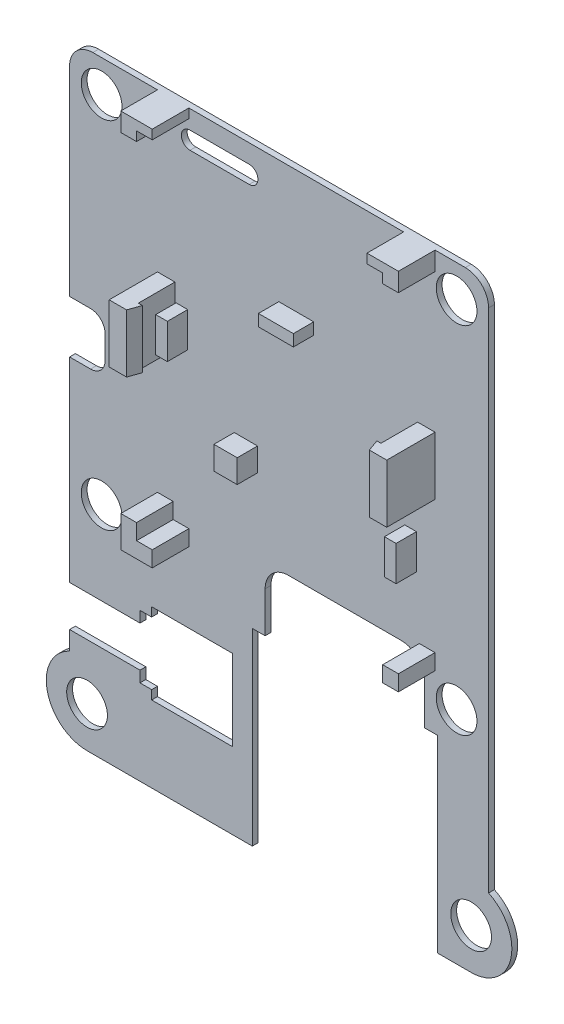
SolidWorks part; units mm, degrees
ref_plane "Front Plane" through (0, 0, 0) normal (0, 0, 1) x (1, 0, 0)
ref_plane "Top Plane" through (0, 0, 0) normal (0, 1, 0) x (1, 0, 0)
ref_plane "Right Plane" through (0, 0, 0) normal (1, 0, 0) x (0, 0, -1)
sketch "Sketch1" plane through (0, 0, 0) normal (0, 0, 1) x (1, 0, 0)
  line L9 (18, -18) -> (-18, -18)
  line L14 (16, 18) -> (-16, 18)
  line L15 (-18, 16) -> (-18, -1.15)
  line L16 (-18, -1.15) -> (-16.2, -1.15)
  line L17 (-14.95, -2.4) -> (-14.95, -4.4)
  line L18 (-16.2, -5.65) -> (-18, -5.65)
  line L19 (-18, -5.65) -> (-18, -18)
  line L20 (-18, -18) -> (-1.2, -18)
  line L21 (-1.2, -18) -> (-1.2, -14.5)
  line L22 (0.8, -12.5) -> (10.5, -12.5)
  line L23 (12.5, -14.5) -> (12.5, -18)
  line L24 (12.5, -18) -> (18, -18)
  line L25 (18, -18) -> (18, 16)
  line L26 (16, 18) -> (-16, 18)
  line L27 (-18, 16) -> (-18, -1.15)
  line L28 (-18, -1.15) -> (-16.2, -1.15)
  line L29 (-14.95, -2.4) -> (-14.95, -4.4)
  line L30 (-16.2, -5.65) -> (-18, -5.65)
  line L31 (-18, -5.65) -> (-18, -18)
  line L32 (-18, -18) -> (-1.2, -18)
  line L33 (-1.2, -18) -> (-1.2, -14.5)
  line L34 (0.8, -12.5) -> (10.5, -12.5)
  line L35 (12.5, -14.5) -> (12.5, -18)
  line L36 (12.5, -18) -> (18, -18)
  line L37 (18, -18) -> (18, 16)
  line L41 (13.6, -18) -> (13.6, -34.2)
  line L42 (13.6, -34.2) -> (16.5, -34.2)
  line L43 (18, -27.5377) -> (18, -18)
  line L44 (18, -18) -> (13.6, -18)
  line L46 (13.6, -18) -> (13.6, -34.2)
  line L47 (13.6, -34.2) -> (16.5, -34.2)
  line L48 (18, -27.5377) -> (18, -18)
  line L49 (18, -18) -> (13.6, -18)
  line L66 (-2.3, -18) -> (-18, -18)
  line L153 (-11.95, -22.43) -> (-11.95, -21.48)
  line L154 (-11.95, -21.48) -> (-10.95, -21.48)
  line L155 (-10.95, -21.48) -> (-10.95, -20.71)
  line L156 (-10.95, -20.71) -> (-4.01, -20.71)
  line L157 (-4.01, -20.71) -> (-4.01, -27.65)
  line L158 (-4.01, -27.65) -> (-10.95, -27.65)
  line L159 (-10.95, -27.65) -> (-10.95, -26.88)
  line L160 (-10.95, -26.88) -> (-11.95, -26.88)
  line L161 (-11.95, -26.88) -> (-11.95, -25.93)
  line L162 (-11.95, -25.93) -> (-18, -25.93)
  line L163 (-18, -25.93) -> (-18, -27.5377)
  line L164 (-16.5, -34.2) -> (-2.3, -34.2)
  line L165 (-2.3, -34.2) -> (-2.3, -18)
  line L166 (-2.3, -18) -> (-18, -18)
  line L167 (-18, -18) -> (-18, -22.43)
  line L168 (-18, -22.43) -> (-11.95, -22.43)
  line L169 (-11.95, -22.43) -> (-11.95, -21.48)
  line L170 (-11.95, -21.48) -> (-10.95, -21.48)
  line L171 (-10.95, -21.48) -> (-10.95, -20.71)
  line L172 (-10.95, -20.71) -> (-4.01, -20.71)
  line L173 (-4.01, -20.71) -> (-4.01, -27.65)
  line L174 (-4.01, -27.65) -> (-10.95, -27.65)
  line L175 (-10.95, -27.65) -> (-10.95, -26.88)
  line L176 (-10.95, -26.88) -> (-11.95, -26.88)
  line L177 (-11.95, -26.88) -> (-11.95, -25.93)
  line L178 (-11.95, -25.93) -> (-18, -25.93)
  line L179 (-18, -25.93) -> (-18, -27.5377)
  line L180 (-16.5, -34.2) -> (-2.3, -34.2)
  line L181 (-2.3, -34.2) -> (-2.3, -18)
  line L182 (-2.3, -18) -> (-18, -18)
  line L183 (-18, -18) -> (-18, -22.43)
  line L184 (-18, -22.43) -> (-11.95, -22.43)
  line L229 (-7.65, 14.9) -> (-2.57, 14.9) construction
  line L230 (-7.65, 16.4) -> (-2.57, 16.4) construction
  line L231 (-7.65, 16.4) -> (-2.57, 16.4)
  line L232 (-7.65, 14.9) -> (-2.57, 14.9)
  circle A2 centre (16.5, -30.7) radius 1.5 construction
  arc A3 (16.5, -34.2) -> (18, -27.5377) centre (16.5, -30.7) ccw
  circle A4 centre (15.25, -15.25) radius 1.75 construction
  circle A5 centre (15.25, 15.25) radius 1.75 construction
  circle A6 centre (-15.25, -15.25) radius 1.75 construction
  arc A7 (-16, 18) -> (-18, 16) centre (-16, 16) ccw
  arc A8 (-14.95, -2.4) -> (-16.2, -1.15) centre (-16.2, -2.4) ccw
  arc A9 (-16.2, -5.65) -> (-14.95, -4.4) centre (-16.2, -4.4) ccw
  arc A10 (0.8, -12.5) -> (-1.2, -14.5) centre (0.8, -14.5) ccw
  arc A11 (12.5, -14.5) -> (10.5, -12.5) centre (10.5, -14.5) ccw
  arc A12 (18, 16) -> (16, 18) centre (16, 16) ccw
  arc A14 (-16, 18) -> (-18, 16) centre (-16, 16) ccw
  arc A15 (-14.95, -2.4) -> (-16.2, -1.15) centre (-16.2, -2.4) ccw
  arc A16 (-16.2, -5.65) -> (-14.95, -4.4) centre (-16.2, -4.4) ccw
  arc A17 (0.8, -12.5) -> (-1.2, -14.5) centre (0.8, -14.5) ccw
  arc A19 (12.5, -14.5) -> (10.5, -12.5) centre (10.5, -14.5) ccw
  arc A20 (18, 16) -> (16, 18) centre (16, 16) ccw
  circle A21 centre (-15.25, 15.25) radius 1.75 construction
  arc A22 (16.5, -34.2) -> (18, -27.5377) centre (16.5, -30.7) ccw
  circle A23 centre (15.25, -15.25) radius 1.75
  circle A24 centre (15.25, 15.25) radius 1.75
  circle A25 centre (-15.25, -15.25) radius 1.75
  circle A26 centre (-15.25, 15.25) radius 1.75
  circle A36 centre (16.5, -30.7) radius 1.5
  circle A54 centre (-16.5, -30.7) radius 1.5 construction
  arc A55 (-18, -27.5377) -> (-16.5, -34.2) centre (-16.5, -30.7) ccw
  arc A56 (-18, -27.5377) -> (-16.5, -34.2) centre (-16.5, -30.7) ccw
  circle A57 centre (-16.5, -30.7) radius 1.5
  arc A62 (-2.57, 14.9) -> (-2.57, 16.4) centre (-2.57, 15.65) ccw construction
  arc A63 (-7.65, 16.4) -> (-7.65, 14.9) centre (-7.65, 15.65) ccw construction
  arc A64 (-7.65, 16.4) -> (-7.65, 14.9) centre (-7.65, 15.65) ccw
  arc A65 (-2.57, 14.9) -> (-2.57, 16.4) centre (-2.57, 15.65) ccw
  circle A69 centre (-16.5, -30.7) radius 1.75
  circle A70 centre (16.5, -30.7) radius 1.75
  dimension "D1" = 0
  dimension "D2" = 0
  dimension "D3" = 0
extrude "Base shape" add sketch "Sketch1" along normal blind 0.5
sketch "Sketch2" plane through (0, 0, 0.5) normal (0, 0, 1) x (1, 0, 0)
  line L0 (1.475, 16.95) -> (1.475, -13.05) construction
  line L1 (-7.85, 1.45) -> (-8.85, 1.45) construction
  line L2 (-0.025, 7.45) -> (2.975, 7.45)
  line L3 (-0.025, 7.45) -> (-0.025, 6.45)
  line L4 (11.8, 16.95) -> (-8.85, 16.95)
  line L5 (-8.85, 16.95) -> (-8.85, -13.05)
  line L6 (-8.85, -13.05) -> (11.8, -13.05)
  line L7 (11.8, -13.05) -> (11.8, 16.95)
  line L8 (11.8, 16.95) -> (-8.85, 16.95)
  line L9 (-8.85, 16.95) -> (-8.85, -13.05)
  line L10 (-8.85, -13.05) -> (11.8, -13.05)
  line L11 (11.8, -13.05) -> (11.8, 16.95)
  line L12 (-0.025, 6.45) -> (2.975, 6.45)
  line L13 (2.975, 7.45) -> (2.975, 6.45)
  line L14 (-0.025, 7.45) -> (2.975, 6.45) construction
  line L15 (-0.025, 6.45) -> (2.975, 7.45) construction
  line L16 (-8.85, 2.95) -> (-7.85, 2.95)
  line L17 (-8.85, 2.95) -> (-8.85, -0.05)
  line L18 (-8.85, -0.05) -> (-7.85, -0.05)
  line L19 (-7.85, 2.95) -> (-7.85, -0.05)
  line L20 (-3.85, -4.2) -> (-1.85, -4.2)
  line L21 (-3.85, -4.2) -> (-3.85, -6.2)
  line L22 (-3.85, -6.2) -> (-1.85, -6.2)
  line L23 (-1.85, -4.2) -> (-1.85, -6.2)
  line L24 (11.8, -3.75) -> (10.8, -3.75)
  line L25 (11.8, -3.75) -> (11.8, -6.75)
  line L26 (11.8, -6.75) -> (10.8, -6.75)
  line L27 (10.8, -3.75) -> (10.8, -6.75)
  line L28 (11.8, 1.95) -> (10.8, 1.95)
  line L29 (11.8, 1.95) -> (11.8, -1.05)
  line L30 (11.8, -1.05) -> (10.8, -1.05)
  line L31 (10.8, 1.95) -> (10.8, -1.05)
  line L32 (-3.85, -5.2) -> (-1.85, -5.2) construction
  line L33 (-2.85, -4.2) -> (-2.85, -6.2) construction
  line L34 (10.8, 0.45) -> (11.8, 0.45) construction
  line L35 (10.8, -5.25) -> (11.8, -5.25) construction
  point P6 (1.475, 6.95)
  dimension "D2" = 3
  dimension "D3" = 1
  dimension "D4" = 10
  dimension "D5" = 7.8
  dimension "D6" = 16.5
  dimension "D7" = 7.85
  dimension "D8" = 6
  dimension "D9" = 2
  dimension "D10" = 15.5
  dimension "D1" = 0
extrude "RX supports" add sketch "Sketch2" along normal blind 1.75 contours L13 L2 L3 L12 | L19 L16 L9 L18 | L23 L20 L21 L22 | L28 L31 L30 L11 | L24 L27 L26 L11
sketch "Sketch3" plane through (0, 0, 0.5) normal (0, 0, 1) x (1, 0, 0)
  line L0 (-8.85, 1.95) -> (11.8, 1.95) construction
  line L1 (1.475, 16.95) -> (1.475, -13.05) construction
  line L2 (-8.95, 4.45) -> (-10.45, 4.45)
  line L3 (-8.95, 4.45) -> (-8.95, -0.55)
  line L4 (11.8, 16.95) -> (-8.85, 16.95)
  line L5 (-8.85, 16.95) -> (-8.85, -13.05)
  line L6 (-8.85, -13.05) -> (11.8, -13.05)
  line L7 (11.8, -13.05) -> (11.8, 16.95)
  line L8 (11.8, 16.95) -> (-8.85, 16.95)
  line L9 (-8.85, 16.95) -> (-8.85, -13.05)
  line L10 (-8.85, -13.05) -> (11.8, -13.05)
  line L11 (11.8, -13.05) -> (11.8, 16.95)
  line L12 (-8.95, -0.55) -> (-10.45, -0.55)
  line L13 (-10.45, 4.45) -> (-10.45, -0.55)
  line L14 (11.9, -0.55) -> (13.4, -0.55)
  line L15 (13.4, 4.45) -> (13.4, -0.55)
  line L16 (11.9, 4.45) -> (13.4, 4.45)
  line L17 (11.9, 4.45) -> (11.9, -0.55)
  point P10 (-10.45, 1.95)
  dimension "D2" = 5
  dimension "D3" = 1.5
  dimension "D4" = 0.1
  dimension "D1" = 0
extrude "Clip base" add sketch "Sketch3" along normal offset from surface (3.15 mm away) 0.2 contours L2 L13 L12 L3 | L16 L17 L14 L15
sketch "Sketch4" plane through (0, 0, 3.65) normal (0, 0, 1) x (1, 0, 0)
  line L0 (-8.95, -0.55) -> (-10.45, -0.55) construction
  line L1 (-10.45, 4.45) -> (-8.6, 4.45)
  line L2 (-10.45, 4.45) -> (-10.45, -0.55)
  line L3 (-10.45, -0.55) -> (-8.6, -0.55)
  line L4 (-8.6, 4.45) -> (-8.6, -0.55)
  line L5 (-8.95, 4.45) -> (-8.95, -0.55) construction
  line L6 (-10.45, 1.95) -> (13.4, 1.95) construction
  line L7 (13.4, 4.45) -> (13.4, -0.55) construction
  line L8 (1.475, 4.45) -> (1.475, -0.55) construction
  line L9 (11.55, 4.45) -> (11.55, -0.55)
  line L10 (13.4, 4.45) -> (11.55, 4.45)
  line L11 (13.4, 4.45) -> (13.4, -0.55)
  line L12 (13.4, -0.55) -> (11.55, -0.55)
  point P17 (1.475, 1.95)
  dimension "D1" = 0.35
extrude "Clip top" add sketch "Sketch4" along normal blind 1
sketch "Sketch5" plane through (0, -0.55, 0) normal (0, -1, 0) x (1, 0, 0)
  line L0 (-8.6, 3.65) -> (-8.95, 4.65)
  line L1 (-10.45, 4.65) -> (-8.6, 4.65) construction
  line L2 (-8.95, 4.65) -> (-8.6, 4.65)
  line L3 (-8.6, 4.65) -> (-8.6, 3.65)
  line L4 (-8.95, 3.65) -> (-8.95, 0.5) construction
  line L5 (11.55, 3.65) -> (11.9, 4.65)
  line L6 (11.55, 4.65) -> (13.4, 4.65) construction
  line L7 (11.9, 4.65) -> (11.55, 4.65)
  line L8 (11.55, 4.65) -> (11.55, 3.65)
  line L9 (11.9, 3.65) -> (11.9, 0.5) construction
extrude "Clip chamfer" cut sketch "Sketch5" against normal up to next
sketch "Sketch6" plane through (0, 0, 0.5) normal (0, 0, 1) x (1, 0, 0)
  line L0 (-10.45, 4.45) -> (-10.45, -0.55) construction
  line L1 (13.4, 4.45) -> (13.4, -0.55) construction
  line L2 (10.7, 18) -> (13.4, 18)
  line L3 (10.7, 18) -> (10.7, 16.4)
  line L4 (10.7, 16.4) -> (13.4, 16.4)
  line L5 (-7.75, -14.65) -> (-10.45, -14.65)
  line L6 (-7.75, -14.65) -> (-7.75, -11.95)
  line L7 (-7.75, -11.95) -> (-10.45, -11.95)
  line L8 (-9.1, -13.3) -> (12.05, -13.3)
  line L9 (12.05, -13.3) -> (12.05, 17.2)
  line L10 (12.05, 17.2) -> (-9.1, 17.2)
  line L11 (-9.1, 17.2) -> (-9.1, -13.3)
  line L12 (-9.1, -13.3) -> (12.05, -13.3)
  line L13 (12.05, -13.3) -> (12.05, 17.2)
  line L14 (12.05, 17.2) -> (-9.1, 17.2)
  line L15 (-9.1, 17.2) -> (-9.1, -13.3)
  line L16 (-10.45, -14.65) -> (-10.45, -11.95)
  line L17 (-7.75, -14.65) -> (-10.45, -11.95) construction
  line L18 (-7.75, -11.95) -> (-10.45, -14.65) construction
  line L19 (13.4, 18) -> (13.4, 16.4)
  line L20 (10.7, 18) -> (13.4, 16.4) construction
  line L21 (10.7, 16.4) -> (13.4, 18) construction
  line L22 (16, 18) -> (-16, 18) construction
  line L23 (-10.45, 4.45) -> (-10.45, -0.55) construction
  line L24 (-10.45, 16.4) -> (-7.75, 16.4)
  line L25 (-10.45, 16.4) -> (-10.45, 18)
  line L26 (-10.45, 18) -> (-7.75, 18)
  line L27 (-7.75, 16.4) -> (-7.75, 18)
  line L28 (-10.45, 16.4) -> (-7.75, 18) construction
  line L29 (-10.45, 18) -> (-7.75, 16.4) construction
  line L31 (12.05, -13.3) -> (13.4, -13.3)
  line L32 (12.05, -13.3) -> (12.05, -11.95)
  line L33 (12.05, -11.95) -> (13.4, -11.95)
  line L34 (13.4, -13.3) -> (13.4, -11.95)
  dimension "D1" = 0.25
extrude "Boss-Extrude1" add sketch "Sketch6" along normal up to surface (3.15 mm away) contours L14 L27 L26 L25 L24 L15 | L19 L2 L3 L14 L13 L4 | L31 L34 L33 L13 | L16 L5 L6 L12 L15 L7 up to face at (-8.775, 1.95, 3.65)
